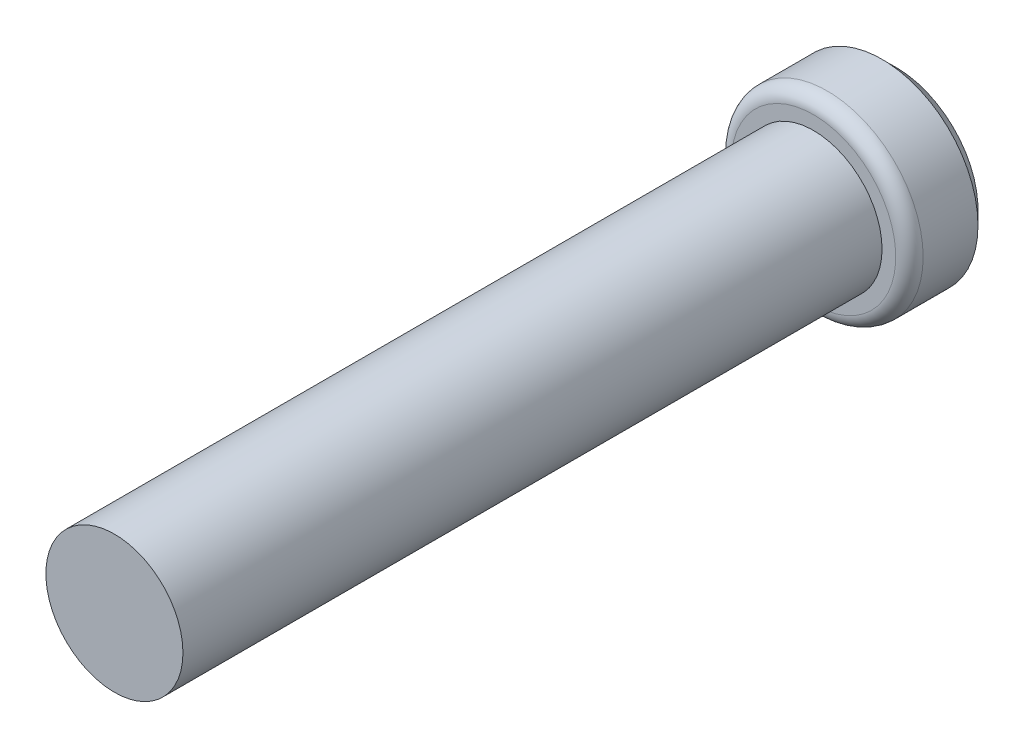
SolidWorks part; units mm, degrees
ref_plane "Front Plane" through (0, 0, 0) normal (0, 0, 1) x (1, 0, 0)
ref_plane "Top Plane" through (0, 0, 0) normal (0, 1, 0) x (1, 0, 0)
ref_plane "Right Plane" through (0, 0, 0) normal (1, 0, 0) x (0, 0, -1)
sketch "Sketch1" plane through (0, 0, 0) normal (0, 0, 1) x (1, 0, 0)
  circle A0 centre (0, 0) radius 4
  circle A1 centre (0, 0) radius 2.5
  dimension "D1" = 5
  dimension "D2" = 8
extrude "Boss-Extrude2" add sketch "Sketch1" along normal blind 25.5 contours A1
sketch "Sketch2" plane through (0, 0, 0) normal (0, 0, -1) x (-1, 0, 0)
  circle A0 centre (0, 0) radius 3.5
  dimension "D1" = 7
extrude "Boss-Extrude3" add sketch "Sketch2" along normal blind 3
sketch "Sketch4" plane through (0, 0, -3) normal (0, 0, -1) x (-1, 0, 0)
  line L0 (0, 2.5173) -> (0, -2.5173)
  line L1 (2.5173, 0) -> (-2.5173, 0)
  line L3 (0, 2.5173) -> (-2.1801, 1.2587)
  line L4 (-2.1801, 1.2587) -> (-2.1801, -1.2587)
  line L5 (-2.1801, -1.2587) -> (0, -2.5173)
  line L6 (0, -2.5173) -> (2.1801, -1.2587)
  line L7 (2.1801, -1.2587) -> (2.1801, 1.2587)
  line L8 (2.1801, 1.2587) -> (0, 2.5173)
  circle A0 centre (0, 0) radius 2.5173
  circle A1 centre (0, 0) radius 2.1801 construction
extrude "Cut-Extrude2" cut sketch "Sketch4" against normal blind 2 contours L6 L7 L1 L0 | L7 L8 L0 L1 | L3 L4 L1 L0 | L4 L5 L0 L1
chamfer "Chamfer2" distance 0.5 angle 45 1 edges at (-3.5, 0, -3)
fillet "Fillet5" radius 0.5 1 edges at (-3.5, 0, 0)
